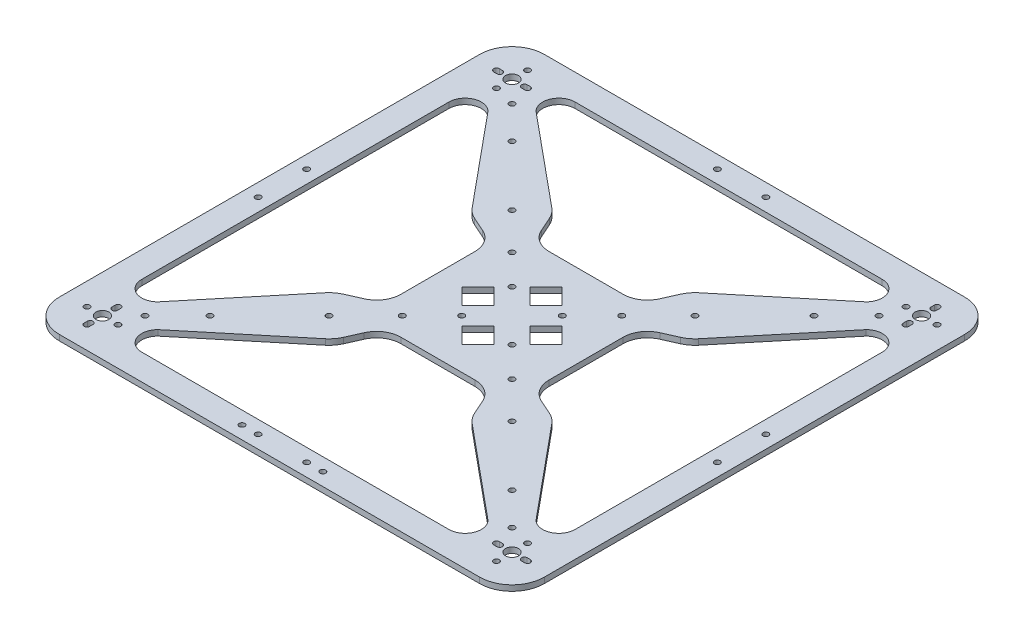
SolidWorks part; units mm, degrees
ref_plane "前视基准面" through (0, 0, 0) normal (0, 0, 1) x (1, 0, 0)
ref_plane "上视基准面" through (0, 0, 0) normal (0, 1, 0) x (1, 0, 0)
ref_plane "右视基准面" through (0, 0, 0) normal (1, 0, 0) x (0, 0, -1)
sketch "草图1" plane through (0, 0, 0) normal (0, 1, 0) x (1, 0, 0)
  line L0 (-1054.8706, 0) -> (-45.8579, 0) construction
  line L1 (0, 1051.8402) -> (0, 45.8579) construction
  line L2 (-782.8818, -782.8818) -> (-112.2626, -112.2626) construction
  line L3 (-118.3308, 118.3308) -> (-106.066, 106.066) construction
  line L4 (-130, 150) -> (130, 150)
  line L5 (150, 130) -> (150, -130)
  line L6 (130, -150) -> (-130, -150)
  line L7 (-150, -130) -> (-150, 130)
  line L8 (-95, 134) -> (95, 134)
  line L12 (-134, 95) -> (-134, -95)
  line L17 (95, -134) -> (-95, -134)
  line L21 (134, -95) -> (134, 95)
  line L23 (-81.4577, 130.6743) -> (-132.4847, 79.6473) construction
  line L24 (-22.9117, 45.8579) -> (31, 45.8579)
  line L25 (-45.8579, 22.9117) -> (-45.8579, -22.9117)
  line L26 (-22.9117, -45.8579) -> (31, -45.8579)
  line L27 (45.8579, 31) -> (45.8579, -31)
  line L28 (-24.1522, 88.9849) -> (-88.9849, 24.1522) construction
  line L29 (126.6655, 140.6242) -> (126.6655, 114.1421) construction
  line L30 (112.4672, 126.6655) -> (140.9628, 126.6655) construction
  line L55 (-17, 17.3333) -> (-17, 17)
  line L58 (-3.3333, 3.3333) -> (-3, 3.3333)
  line L62 (3, 3.3333) -> (3.3333, 3.3333)
  line L69 (-3, -2.3333) -> (-3, -3)
  line L70 (-17, -16.3333) -> (-16.3333, -16.3333)
  line L71 (3, -2.3333) -> (3, -3)
  line L74 (16.3333, -16.3333) -> (17, -16.3333)
  line L259 (126.6655, 136.2905) -> (126.6655, 134.2905) construction
  line L260 (128.4155, 136.2905) -> (128.4155, 134.2905)
  line L261 (124.9155, 136.2905) -> (124.9155, 134.2905)
  line L262 (126.6655, 117.0405) -> (126.6655, 119.0405) construction
  line L267 (128.4155, 117.0405) -> (128.4155, 119.0405)
  line L268 (124.9155, 117.0405) -> (124.9155, 119.0405)
  line L269 (126.6655, -136.2905) -> (126.6655, -134.2905) construction
  line L270 (128.4155, -136.2905) -> (128.4155, -136.13)
  line L271 (124.9155, -136.2905) -> (124.9155, -136.13)
  line L272 (126.6655, -117.0405) -> (126.6655, -119.0405) construction
  line L273 (128.4155, -117.0405) -> (128.4155, -117.2009)
  line L274 (124.9155, -117.0405) -> (124.9155, -117.2009)
  line L443 (-54.7685, 36.6201) -> (-63.6728, 40.5754)
  line L444 (-95, -134) -> (95, -134)
  line L446 (-22.9117, -45.8579) -> (31, -45.8579)
  line L448 (45.8579, 0) -> (61.7845, 0) construction
  line L450 (32.7037, -32.7037) -> (35.1786, -35.1786) construction
  line L451 (-758.372, -758.372) -> (-54.2933, -54.2933) construction
  line L452 (0, -45.8579) -> (0, -290.6315) construction
  line L487 (112.2626, 112.2626) -> (736.0796, 736.0796) construction
  line L488 (-67.9756, 67.9756) -> (-17, 17) construction
  line L489 (-67.9756, -67.9756) -> (-16.3333, -16.3333) construction
  line L490 (-80.35, -80.35) -> (-75.7538, -75.7538) construction
  line L491 (78.9358, -78.9358) -> (86.7139, -86.7139) construction
  line L492 (93.4315, -93.4315) -> (221.7809, -221.7809) construction
  line L493 (-126.6655, 136.2905) -> (-126.6655, 134.2905) construction
  line L494 (-128.4155, 136.2905) -> (-128.4155, 136.13)
  line L495 (-124.9155, 136.2905) -> (-124.9155, 136.13)
  line L496 (-126.6655, 117.0405) -> (-126.6655, 119.0405) construction
  line L497 (-128.4155, 117.0405) -> (-128.4155, 117.2009)
  line L498 (-124.9155, 117.0405) -> (-124.9155, 117.2009)
  line L499 (-126.6655, -136.2905) -> (-126.6655, -134.2905) construction
  line L500 (-128.4155, -136.2905) -> (-128.4155, -134.2905)
  line L501 (-124.9155, -136.2905) -> (-124.9155, -134.2905)
  line L502 (-126.6655, -117.0405) -> (-126.6655, -119.0405) construction
  line L503 (-128.4155, -117.0405) -> (-128.4155, -119.0405)
  line L504 (-124.9155, -117.0405) -> (-124.9155, -119.0405)
  line L505 (0, 30.799) -> (-9.8995, 20.8995)
  line L506 (-9.8995, 20.8995) -> (0, 11)
  line L507 (0, 11) -> (9.8995, 20.8995)
  line L508 (9.8995, 20.8995) -> (0, 30.799)
  line L509 (0, -11) -> (9.8995, -20.8995)
  line L510 (-9.8995, -20.8995) -> (0, -11)
  line L511 (0, -30.799) -> (-9.8995, -20.8995)
  line L512 (9.8995, -20.8995) -> (0, -30.799)
  line L513 (-11, 0) -> (-20.8995, -9.8995)
  line L514 (-20.8995, 9.8995) -> (-11, 0)
  line L515 (-30.799, 0) -> (-20.8995, 9.8995)
  line L516 (-20.8995, -9.8995) -> (-30.799, 0)
  line L518 (-95, 134) -> (95, 134)
  line L520 (-22.9117, 45.8579) -> (31, 45.8579)
  line L521 (11, 0) -> (20.8995, 9.8995)
  line L522 (20.8995, -9.8995) -> (11, 0)
  line L523 (30.799, 0) -> (20.8995, -9.8995)
  line L524 (20.8995, 9.8995) -> (30.799, 0)
  line L525 (89.5424, 97.3205) -> (97.3205, 89.5424) construction
  line L526 (-136.2905, 126.6655) -> (-134.2905, 126.6655) construction
  line L527 (-109.9551, -102.1769) -> (-102.1769, -109.9551) construction
  line L528 (-136.2905, 128.4155) -> (-134.2905, 128.4155)
  line L529 (-136.2905, 124.9155) -> (-134.2905, 124.9155)
  line L530 (-126.6655, 136.2905) -> (-126.6655, 134.2905) construction
  line L531 (-124.9155, 136.2905) -> (-124.9155, 136.13)
  line L532 (-128.4155, 136.2905) -> (-128.4155, 136.13)
  line L533 (-117.0405, 126.6655) -> (-119.0405, 126.6655) construction
  line L534 (-117.0405, 124.9155) -> (-119.0405, 124.9155)
  line L535 (-117.0405, 128.4155) -> (-119.0405, 128.4155)
  line L536 (117.0405, -126.6655) -> (119.0405, -126.6655) construction
  line L537 (117.0405, -128.4155) -> (119.0405, -128.4155)
  line L538 (117.0405, -124.9155) -> (119.0405, -124.9155)
  line L539 (126.6655, -117.0405) -> (126.6655, -119.0405) construction
  line L540 (124.9155, -117.0405) -> (124.9155, -117.2009)
  line L541 (128.4155, -117.0405) -> (128.4155, -117.2009)
  line L542 (136.2905, -126.6655) -> (134.2905, -126.6655) construction
  line L543 (136.2905, -124.9155) -> (134.2905, -124.9155)
  line L544 (136.2905, -128.4155) -> (134.2905, -128.4155)
  line L545 (-4, 142) -> (15, 142) construction
  line L546 (-70.0519, -45.4129) -> (-116.9289, -102.0711)
  line L548 (-54.7685, -36.6201) -> (-63.6728, -40.5754)
  line L549 (-36.6201, -54.7685) -> (-40.5754, -63.6728)
  line L550 (-45.4129, -70.0519) -> (-102.0711, -116.9289)
  line L551 (-36.6201, 54.7685) -> (-40.5754, 63.6728)
  line L552 (-70.0519, 45.4129) -> (-116.9289, 102.0711)
  line L553 (-45.4129, 70.0519) -> (-102.0711, 116.9289)
  line L554 (36.6201, 54.7685) -> (40.5754, 63.6728)
  line L555 (54.7685, 36.6201) -> (63.6728, 40.5754)
  line L556 (45.4129, 70.0519) -> (102.0711, 116.9289)
  line L557 (70.0519, 45.4129) -> (116.9289, 102.0711)
  line L558 (54.7685, -36.6201) -> (63.6728, -40.5754)
  line L559 (36.6201, -54.7685) -> (40.5754, -63.6728)
  line L560 (70.0519, -45.4129) -> (116.9289, -102.0711)
  line L561 (45.4129, -70.0519) -> (102.0711, -116.9289)
  line L562 (-113.4949, 98.6371) -> (-116.9289, 102.0711)
  line L563 (-98.6371, 113.4949) -> (-102.0711, 116.9289)
  line L564 (-98.6371, 113.4949) -> (-102.0711, 116.9289)
  arc A6 (95, 134) -> (102.0711, 116.9289) centre (95, 124) cw
  arc A7 (-95, 134) -> (-102.0711, 116.9289) centre (-95, 124) ccw
  arc A9 (-116.9289, -102.0711) -> (-134, -95) centre (-124, -95) cw
  arc A10 (-134, 95) -> (-116.9289, 102.0711) centre (-124, 95) cw
  arc A11 (102.0711, -116.9289) -> (95, -134) centre (95, -124) cw
  arc A13 (-102.0711, -116.9289) -> (-95, -134) centre (-95, -124) ccw
  arc A17 (130, 150) -> (150, 130) centre (130, 130) cw
  arc A18 (150, -130) -> (130, -150) centre (130, -130) cw
  arc A19 (-150, -130) -> (-130, -150) centre (-130, -130) ccw
  arc A20 (-130, 150) -> (-150, 130) centre (-130, 130) ccw
  arc A33 (134, -95) -> (116.9289, -102.0711) centre (124, -95) cw
  arc A35 (134, 95) -> (116.9289, 102.0711) centre (124, 95) ccw
  circle A52 centre (126.6655, 126.6655) radius 9.625 construction
  circle A53 centre (-126.6655, 126.6655) radius 9.625 construction
  circle A54 centre (-126.6655, -126.6655) radius 9.625 construction
  circle A55 centre (126.6655, -126.6655) radius 9.625 construction
  circle A72 centre (126.6655, 126.6655) radius 4
  circle A73 centre (-126.6655, 126.6655) radius 4
  circle A74 centre (126.6655, -126.6655) radius 4
  circle A75 centre (-126.6655, -126.6655) radius 4
  circle A76 centre (-15, 142) radius 1.75
  circle A77 centre (15, 142) radius 1.75
  circle A78 centre (-142, -15) radius 1.75
  circle A79 centre (-142, 15) radius 1.75
  circle A80 centre (15, -142) radius 1.75
  circle A81 centre (-15, -142) radius 1.75
  circle A82 centre (142, 15) radius 1.75
  circle A83 centre (142, -15) radius 1.75
  circle A84 centre (-33.9411, 33.9411) radius 1.75
  circle A86 centre (33.9411, 33.9411) radius 1.75
  circle A87 centre (33.9411, -33.9411) radius 1.75
  circle A88 centre (-33.9411, -33.9411) radius 1.75
  arc A89 (-95, -134) -> (-102.0711, -116.9289) centre (-95, -124) cw
  arc A90 (95, -134) -> (102.0711, -116.9289) centre (95, -124) ccw
  circle A91 centre (-113.5, 113.5) radius 1.75
  circle A92 centre (-113.5, -113.5) radius 1.75
  circle A93 centre (113.5, 113.5) radius 1.75
  circle A94 centre (113.5, -113.5) radius 1.75
  circle A133 centre (136.2905, 126.6655) radius 1.75
  arc A134 (128.4155, 136.2905) -> (124.9155, 136.2905) centre (126.6655, 136.2905) ccw
  arc A135 (124.9155, 134.2905) -> (128.4155, 134.2905) centre (126.6655, 134.2905) ccw
  circle A140 centre (117.0405, 126.6655) radius 1.75
  arc A141 (128.4155, 117.0405) -> (124.9155, 117.0405) centre (126.6655, 117.0405) cw
  arc A142 (124.9155, 119.0405) -> (128.4155, 119.0405) centre (126.6655, 119.0405) cw
  arc A143 (128.4155, -136.2905) -> (124.9155, -136.2905) centre (126.6655, -136.2905) cw
  arc A145 (128.4155, -117.0405) -> (124.9155, -117.0405) centre (126.6655, -117.0405) ccw
  arc A147 (117.1996, -124.9227) -> (117.1996, -128.4082) centre (117.0405, -126.6655) ccw
  arc A148 (136.1314, -124.9227) -> (136.1314, -128.4082) centre (136.2905, -126.6655) cw
  arc A149 (-128.4155, 136.2905) -> (-124.9155, 136.2905) centre (-126.6655, 136.2905) cw
  arc A151 (-128.4155, 117.0405) -> (-124.9155, 117.0405) centre (-126.6655, 117.0405) ccw
  arc A153 (-136.1314, 124.9227) -> (-136.1314, 128.4082) centre (-136.2905, 126.6655) cw
  arc A154 (-117.1996, 124.9227) -> (-117.1996, 128.4082) centre (-117.0405, 126.6655) ccw
  arc A155 (-128.4155, -136.2905) -> (-124.9155, -136.2905) centre (-126.6655, -136.2905) ccw
  arc A156 (-124.9155, -134.2905) -> (-128.4155, -134.2905) centre (-126.6655, -134.2905) ccw
  arc A157 (-128.4155, -117.0405) -> (-124.9155, -117.0405) centre (-126.6655, -117.0405) cw
  arc A158 (-124.9155, -119.0405) -> (-128.4155, -119.0405) centre (-126.6655, -119.0405) cw
  circle A159 centre (-136.2905, -126.6655) radius 1.75
  circle A160 centre (-117.0405, -126.6655) radius 1.75
  arc A161 (-95, 134) -> (-102.0711, 116.9289) centre (-95, 124) ccw
  arc A162 (102.0711, 116.9289) -> (95, 134) centre (95, 124) ccw
  circle A164 centre (93.4315, 93.4315) radius 1.75
  circle A167 centre (-56.5685, 56.5685) radius 1.75
  circle A168 centre (-56.5685, -56.5685) radius 1.75
  circle A169 centre (56.5685, 56.5685) radius 1.75
  circle A170 centre (56.5685, -56.5685) radius 1.75
  circle A171 centre (-93.4315, 93.4315) radius 1.75
  circle A172 centre (-93.4315, -93.4315) radius 1.75
  circle A173 centre (93.4315, -93.4315) radius 1.75
  circle A174 centre (-15.5563, 15.5563) radius 1.75
  circle A175 centre (-15.5563, -15.5563) radius 1.75
  circle A176 centre (15.5563, 15.5563) radius 1.75
  circle A177 centre (15.5563, -15.5563) radius 1.75
  arc A178 (-136.2905, 128.4155) -> (-136.2905, 124.9155) centre (-136.2905, 126.6655) ccw
  arc A179 (-134.2905, 124.9155) -> (-134.2905, 128.4155) centre (-134.2905, 126.6655) ccw
  arc A180 (-124.9155, 136.2905) -> (-128.4155, 136.2905) centre (-126.6655, 136.2905) ccw
  arc A182 (-117.0405, 124.9155) -> (-117.0405, 128.4155) centre (-117.0405, 126.6655) ccw
  arc A183 (-119.0405, 128.4155) -> (-119.0405, 124.9155) centre (-119.0405, 126.6655) ccw
  circle A184 centre (-126.6655, 136.2905) radius 1.75
  arc A185 (-117.1996, 128.4082) -> (-117.1996, 124.9227) centre (-117.0405, 126.6655) cw
  circle A186 centre (-126.6655, 117.0405) radius 1.75
  arc A187 (117.0405, -128.4155) -> (117.0405, -124.9155) centre (117.0405, -126.6655) cw
  arc A188 (119.0405, -124.9155) -> (119.0405, -128.4155) centre (119.0405, -126.6655) cw
  arc A189 (124.9155, -117.0405) -> (128.4155, -117.0405) centre (126.6655, -117.0405) cw
  arc A191 (136.2905, -124.9155) -> (136.2905, -128.4155) centre (136.2905, -126.6655) cw
  arc A192 (134.2905, -128.4155) -> (134.2905, -124.9155) centre (134.2905, -126.6655) cw
  circle A193 centre (126.6655, -136.2905) radius 1.75
  arc A194 (117.1996, -128.4082) -> (117.1996, -124.9227) centre (117.0405, -126.6655) cw
  circle A195 centre (126.6655, -117.0405) radius 1.75
  circle A198 centre (-25, -142) radius 1.75
  circle A199 centre (25, -142) radius 1.75
  arc A200 (-63.6728, -40.5754) -> (-70.0519, -45.4129) centre (-56.5685, -56.5685) ccw
  arc A201 (-45.4129, -70.0519) -> (-40.5754, -63.6728) centre (-56.5685, -56.5685) ccw
  arc A202 (-54.7685, -36.6201) -> (-45.8579, -22.9117) centre (-60.8579, -22.9117) ccw
  arc A203 (-36.6201, -54.7685) -> (-22.9117, -45.8579) centre (-22.9117, -60.8579) cw
  arc A204 (-54.7685, 36.6201) -> (-45.8579, 22.9117) centre (-60.8579, 22.9117) cw
  arc A205 (-36.6201, 54.7685) -> (-22.9117, 45.8579) centre (-22.9117, 60.8579) ccw
  arc A206 (-70.0519, 45.4129) -> (-63.6728, 40.5754) centre (-56.5685, 56.5685) ccw
  arc A207 (-40.5754, 63.6728) -> (-45.4129, 70.0519) centre (-56.5685, 56.5685) ccw
  arc A208 (36.6201, 54.7685) -> (22.9117, 45.8579) centre (22.9117, 60.8579) cw
  arc A209 (54.7685, 36.6201) -> (45.8579, 22.9117) centre (60.8579, 22.9117) ccw
  arc A210 (45.4129, 70.0519) -> (40.5754, 63.6728) centre (56.5685, 56.5685) ccw
  arc A211 (63.6728, 40.5754) -> (70.0519, 45.4129) centre (56.5685, 56.5685) ccw
  arc A212 (54.7685, -36.6201) -> (45.8579, -22.9117) centre (60.8579, -22.9117) cw
  arc A213 (36.6201, -54.7685) -> (22.9117, -45.8579) centre (22.9117, -60.8579) ccw
  arc A214 (70.0519, -45.4129) -> (63.6728, -40.5754) centre (56.5685, -56.5685) ccw
  arc A215 (40.5754, -63.6728) -> (45.4129, -70.0519) centre (56.5685, -56.5685) ccw
  point P40 (0, 14.8579)
  point P43 (119.1421, 134)
  point P46 (-119.1421, 134)
  point P49 (-14.8579, 0)
  point P52 (-134, -119.1421)
  point P55 (-134, 119.1421)
  point P58 (119.1421, -134)
  point P61 (0, -14.8579)
  point P64 (-119.1421, -134)
  point P70 (134, -119.1421)
  point P73 (134, 119.1421)
  point P76 (150, 150)
  point P79 (150, -150)
  point P82 (-150, -150)
  point P85 (-150, 150)
  point P118 (126.6655, 135.2905)
  point P127 (126.6655, 118.0405)
  point P134 (126.6655, -135.2905)
  point P141 (126.6655, -118.0405)
  point P193 (-135.2905, 126.6655)
  point P202 (-126.6655, 135.2905)
  point P211 (-118.0405, 126.6655)
  point P231 (-126.6655, 135.2905)
  point P237 (126.6655, -118.0405)
  point P240 (-126.6655, 118.0405)
  point P252 (-126.6655, -135.2905)
  point P259 (-126.6655, -118.0405)
  point P268 (-126.6655, 126.6655)
  point P275 (-126.6655, 126.6655)
  point P277 (118.0405, -126.6655)
  point P293 (126.6655, -118.0405)
  point P300 (135.2905, -126.6655)
  point P305 (126.6655, -126.6655)
  point P315 (126.6655, -126.6655)
  point P321 (0, 142)
  point P369 (0, 0)
  dimension "D2" = 190
  dimension "D3" = 62
  dimension "D5" = 268
  dimension "D7" = 22
  dimension "D10" = 35
  dimension "D11" = 3.5
  dimension "D12" = 10
  dimension "D13" = 19.25
  dimension "D14" = 20
  dimension "D15" = 33
  dimension "D17" = 1.75
  dimension "D18" = 8
  dimension "D19" = 3.5
  dimension "D33" = 3.5
  dimension "D21" = 3.5
  dimension "D32" = 4
  dimension "D36" = 80
  dimension "D23" = 2
  dimension "D25" = 3.5
  dimension "D28" = 4
  dimension "D29" = 3.5
  dimension "D30" = 4
  dimension "D31" = 30
  dimension "D6" = 3.5
  dimension "D4" = 300
  dimension "D8" = 80
  dimension "D9" = 80
  dimension "D16" = 91.7157
  dimension "D20" = 48
  dimension "D22" = 36.5
  dimension "D24" = 45
  dimension "D26" = 14
  dimension "D27" = 11
  dimension "D34" = 8
  dimension "D35" = 15
extrude "凸台-拉伸1" add sketch "草图1" along normal blind 3.5
